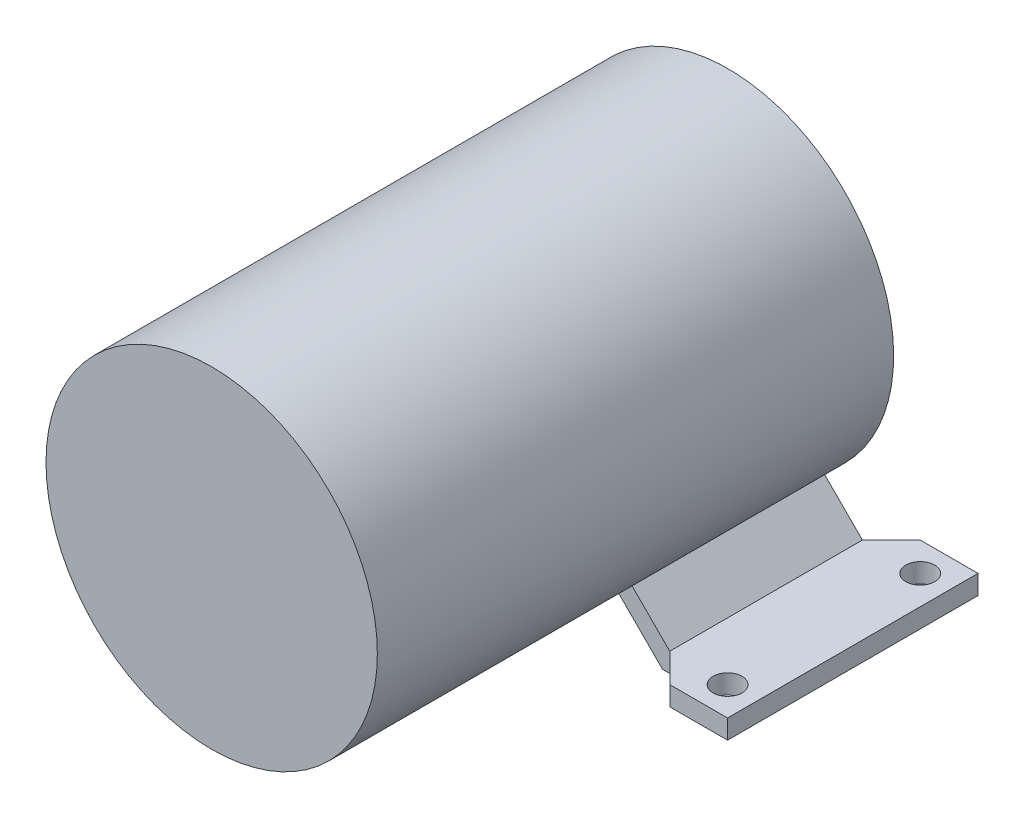
SolidWorks part; units mm, degrees
ref_plane "Front Plane" through (0, 0, 0) normal (0, 0, 1) x (1, 0, 0)
ref_plane "Top Plane" through (0, 0, 0) normal (0, 1, 0) x (1, 0, 0)
ref_plane "Right Plane" through (0, 0, 0) normal (1, 0, 0) x (0, 0, -1)
sketch "Sketch1" plane through (0, 0, 0) normal (0, 0, 1) x (1, 0, 0)
  circle A0 centre (0, 0) radius 54.61
  dimension "D1" = 109.22
extrude "Boss-Extrude1" add sketch "Sketch1" along normal blind 170.18 contours A0
sketch "Sketch2" plane through (0, 0, 170.18) normal (0, 0, 1) x (1, 0, 0)
  circle A0 centre (0, 0) radius 6.35
  dimension "D1" = 12.7
extrude "Boss-Extrude2" add sketch "Sketch2" against normal blind 25.4 from surface at -170.18 starting at face at (54.61, 0, 0)
sketch "Sketch3" plane through (0, 0, 0) normal (0, 0, 1) x (1, 0, 0)
  line L0 (-31.288, -44.7584) -> (-44.3146, -57.785)
  line L1 (-25.8808, -48.0878) -> (-41.928, -64.135)
  line L2 (-44.3146, -57.785) -> (-47.4896, -57.785)
  line L3 (-47.4896, -57.785) -> (-47.4896, -64.135)
  line L4 (-47.4896, -64.135) -> (-41.928, -64.135)
  line L5 (-1000, 0) -> (49000, 0) construction
  line L6 (0, 0) -> (-77.1605, -77.1605) construction
  line L7 (-1000, -54.61) -> (49000, -54.61) construction
  circle A0 centre (0, 0) radius 54.61 construction
  arc A1 (-31.288, -44.7584) -> (-25.8808, -48.0878) centre (0, 0) ccw
  dimension "D3" = 6.35
  dimension "D4" = 3.175
  dimension "D1" = 45
  dimension "D2" = 6.35
  dimension "D5" = 3.175
  dimension "D6" = 9.525
extrude "Boss-Extrude3" add sketch "Sketch3" along normal blind 63.5
sketch "Sketch4" plane through (0, -57.785, 0) normal (0, 1, 0) x (1, 0, 0)
  line L0 (-53.8396, -73.025) -> (-44.3146, -63.5)
  line L1 (-53.8396, 9.525) -> (-72.8896, 9.525)
  line L2 (-72.8896, 9.525) -> (-72.8896, -73.025)
  line L3 (-72.8896, -73.025) -> (-53.8396, -73.025)
  line L4 (-44.3146, 0) -> (-47.4896, 0)
  line L5 (-47.4896, 0) -> (-47.4896, -63.5)
  line L6 (-47.4896, -63.5) -> (-44.3146, -63.5)
  line L7 (-44.3146, -63.5) -> (-44.3146, 0)
  line L8 (-44.3146, 0) -> (-47.4896, 0)
  line L9 (-47.4896, 0) -> (-47.4896, -63.5)
  line L10 (-47.4896, -63.5) -> (-44.3146, -63.5)
  line L11 (-44.3146, -63.5) -> (-44.3146, 0)
  line L12 (-53.8396, 9.525) -> (-44.3146, 0)
  line L13 (-31.288, 0) -> (-44.3146, 0) construction
  line L14 (54.61, 0) -> (-54.61, 0) construction
  circle A0 centre (-63.3646, 0) radius 4.7625
  circle A1 centre (-63.3646, -63.5) radius 4.7625
  dimension "D5" = 9.525
  dimension "D2" = 135
  dimension "D3" = 82.55
  dimension "D4" = 28.575
  dimension "D6" = 9.525
  dimension "D1" = 0
extrude "Boss-Extrude4" add sketch "Sketch4" against normal up to surface (6.35 mm away)
mirror "Mirror1" about plane through (0, 0, 0) normal (1, 0, 0) of bodies 104
equation "\"D3@Sketch3\"=\"D2@Sketch3\""
